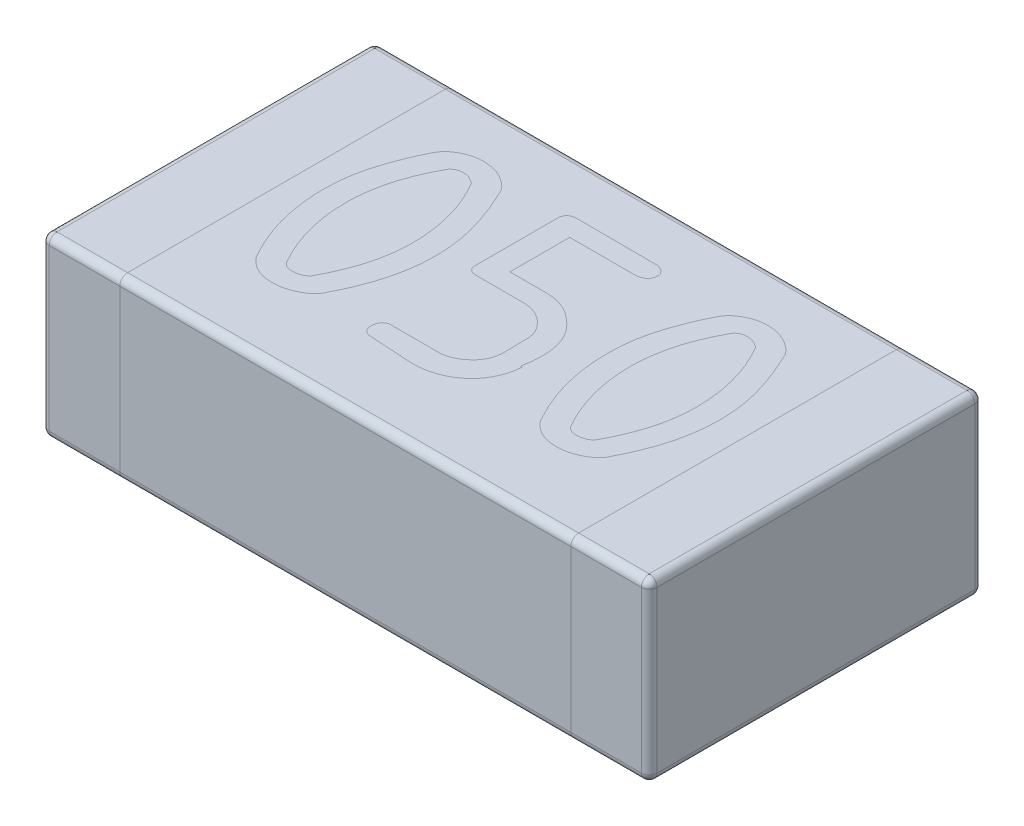
SolidWorks part; units mm, degrees
ref_plane "Front Plane" through (0, 0, 0) normal (0, 0, 1) x (1, 0, 0)
ref_plane "Top Plane" through (0, 0, 0) normal (0, 1, 0) x (1, 0, 0)
ref_plane "Right Plane" through (0, 0, 0) normal (1, 0, 0) x (0, 0, -1)
sketch "Sketch1" plane through (0, 0, 0) normal (0, 1, 0) x (1, 0, 0)
  line L1 (-0.755, -0.425) -> (0.755, -0.425)
  line L2 (-0.775, -0.405) -> (-0.775, 0.405)
  line L3 (-0.755, 0.425) -> (0.755, 0.425)
  line L4 (0.775, -0.405) -> (0.775, 0.405)
  line L5 (-0.775, -0.425) -> (0.775, 0.425) construction
  line L6 (-0.775, 0.425) -> (0.775, -0.425) construction
  arc A4 (-0.775, -0.405) -> (-0.755, -0.425) centre (-0.755, -0.405) ccw
  arc A5 (0.755, -0.425) -> (0.775, -0.405) centre (0.755, -0.405) ccw
  arc A6 (0.775, 0.405) -> (0.755, 0.425) centre (0.755, 0.405) ccw
  arc A7 (-0.755, 0.425) -> (-0.775, 0.405) centre (-0.755, 0.405) ccw
  point P0 (0, 0)
  dimension "D4" = 0.02
  dimension "D1" = 1.55
  dimension "D2" = 0.85
extrude "Boss-Extrude1" add sketch "Sketch1" along normal mid plane 0.45
sketch "Sketch3" plane through (0, 0.225, 0) normal (0, 1, 0) x (1, 0, 0)
  line L0 (-0.575, 0) -> (0.575, 0) construction
  line L1 (-0.575, -0.5133) -> (-0.575, 0.5133)
  line L2 (0.575, -0.5133) -> (0.575, 0.5133)
  line L3 (0, -0.25) -> (0, 0.25) construction
  line L6 (-0.575, -0.25) -> (0.575, -0.25) construction
  text T0 "<b>050</b>\r\n" font "SWIsop1" height 0.53
  point P4 (0, 0)
  point P8 (-0.575, 0)
  point P11 (0.575, 0)
  point P14 (0, 0)
  point P17 (0, -0.25)
  dimension "D1" = 1.15
  dimension "D2" = 0.5
sketch "Sketch4" plane through (0, 0, 0.425) normal (0, 0, 1) x (1, 0, 0)
  line L0 (-0.575, 0.225) -> (-0.575, -0.5946)
  line L1 (0.575, 0.225) -> (0.575, -0.5946)
sketch "Sketch5" plane through (0, 0, -0.425) normal (0, 0, -1) x (-1, 0, 0)
  line L0 (-0.575, 0.225) -> (-0.575, -0.5946) construction
  line L1 (-0.575, 0.225) -> (-0.575, -0.5946)
  line L2 (0.575, 0.225) -> (0.575, -0.5946) construction
  line L3 (0.575, 0.225) -> (0.575, -0.5946)
sketch "Sketch6" plane through (0, -0.225, 0) normal (0, -1, 0) x (1, 0, 0)
  line L0 (0.575, 0.5133) -> (0.575, -0.5133) construction
  line L1 (-0.575, 0.5133) -> (-0.575, -0.5133) construction
  line L2 (0.575, 0.5133) -> (0.575, -0.5133)
  line L3 (-0.575, 0.5133) -> (-0.575, -0.5133)
split line "Split Line2"
split line "Split Line3"
split line "Split Line4"
split line "Split Line5"
fillet "Fillet2" radius 0.02 24 edges at (-0.665, -0.225, 0.425) (0, -0.225, 0.425) (0.665, -0.225, 0.425) (-0.7691, -0.225, 0.4191) (-0.775, -0.225, 0) (-0.7691, -0.225, -0.4191) (0.665, -0.225, -0.425) (0, -0.225, -0.425) (-0.665, -0.225, -0.425) (0.7691, -0.225, -0.4191) (0.775, -0.225, 0) (0.7691, -0.225, 0.4191) (-0.7691, 0.225, 0.4191) (-0.775, 0.225, 0) (-0.7691, 0.225, -0.4191) (0.665, 0.225, -0.425) (0, 0.225, -0.425) (-0.665, 0.225, -0.425) (0.7691, 0.225, -0.4191) (0.775, 0.225, 0) (0.7691, 0.225, 0.4191) (-0.665, 0.225, 0.425) (0, 0.225, 0.425) (0.665, 0.225, 0.425)
